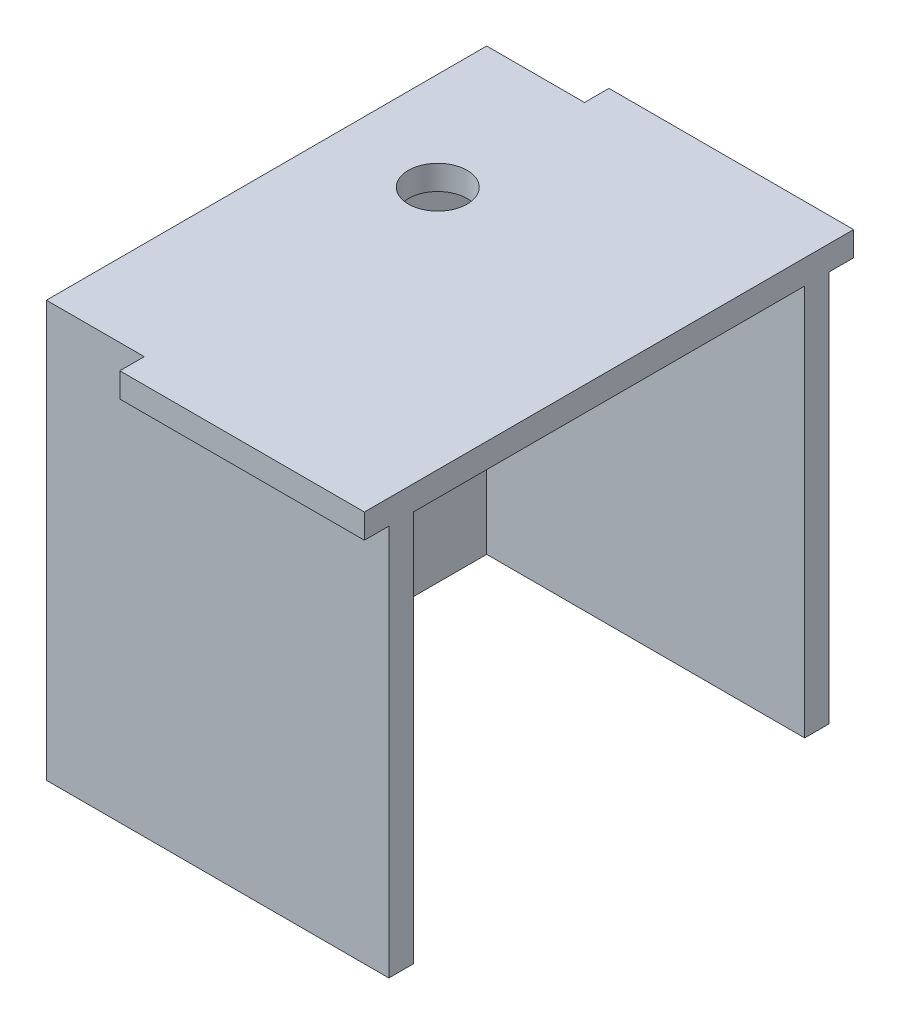
SolidWorks part; units mm, degrees
material "CA"
ref_plane "Front Plane" through (0, 0, 0) normal (0, 0, 1) x (1, 0, 0)
ref_plane "Top Plane" through (0, 0, 0) normal (0, 1, 0) x (1, 0, 0)
ref_plane "Right Plane" through (0, 0, 0) normal (1, 0, 0) x (0, 0, -1)
sketch "Sketch1" plane through (0, 0, 0) normal (0, 0, 1) x (1, 0, 0)
  line L1 (0, 0) -> (-65, 0)
  line L2 (0, 0) -> (0, 5)
  line L3 (0, 5) -> (-65, 5)
  line L6 (-65, 5) -> (-65, 30)
  line L7 (-65, 30) -> (-70, 30)
  line L8 (-70, 0) -> (-70, 30)
  line L10 (-65, 0) -> (-65, -80)
  line L11 (-65, -80) -> (-70, -80)
  line L12 (-70, 0) -> (-70, -80)
  dimension "D1" = 5
  dimension "D2" = 5
  dimension "D3" = 65
  dimension "D4" = 30
  dimension "D5" = 80
extrude "Boss-Extrude1" add sketch "Sketch1" along normal blind 100
sketch "Sketch2" plane through (0, 0, 100) normal (0, 0, 1) x (1, 0, 0)
  line L10 (-65, 0) -> (-70, 0)
  line L11 (-65, 0) -> (-65, -80)
  line L12 (-65, -80) -> (-70, -80)
  line L13 (-70, 0) -> (-70, -80)
extrude "Cut-Extrude2" cut sketch "Sketch2" against normal blind 5
sketch "Sketch3" plane through (0, 0, 0) normal (0, 0, -1) x (-1, 0, 0)
  line L1 (65, 0) -> (70, 0)
  line L2 (65, 0) -> (65, -80)
  line L3 (65, -80) -> (70, -80)
  line L4 (70, 0) -> (70, -80)
extrude "Cut-Extrude3" cut sketch "Sketch3" against normal blind 5
sketch "Sketch4" plane through (0, 0, 100) normal (0, 0, 1) x (1, 0, 0)
  line L0 (-70, 0) -> (0, 0) construction
  line L1 (-65, 5) -> (-50, 5)
  line L2 (-65, 5) -> (-65, 0)
  line L3 (-65, 0) -> (-50, 0)
  line L4 (-50, 5) -> (-50, 0)
  dimension "D1" = 15
extrude "Cut-Extrude4" cut sketch "Sketch4" against normal blind 5
sketch "Sketch5" plane through (0, 0, 0) normal (0, 0, -1) x (-1, 0, 0)
  line L0 (70, 0) -> (0, 0) construction
  line L1 (65, 5) -> (50, 5)
  line L2 (65, 5) -> (65, 0)
  line L3 (65, 0) -> (50, 0)
  line L4 (50, 5) -> (50, 0)
  dimension "D1" = 15
extrude "Cut-Extrude5" cut sketch "Sketch5" against normal blind 5
sketch "Sketch6" plane through (-65, 0, 0) normal (1, 0, 0) x (0, 0, -1)
  line L0 (-95, 0) -> (-5, 0) construction
  line L1 (-95, -80) -> (-95, 0) construction
  circle A0 centre (-50, -10) radius 1.5
  circle A1 centre (-50, -60.45) radius 1.5
  dimension "D2" = 3
  dimension "D4" = 3
  dimension "D1" = 10
  dimension "D3" = 50.45
  dimension "D5" = 45
  dimension "D6" = 45
extrude "Cut-Extrude6" cut sketch "Sketch6" against normal blind 10
sketch "Sketch7" plane through (-65, 0, 0) normal (1, 0, 0) x (0, 0, -1)
  line L0 (-95, -80) -> (-95, 0) construction
  line L1 (-95, -14.175) -> (-28.95, -14.175)
  line L2 (-95, -14.175) -> (-95, -56.275)
  line L3 (-95, -56.275) -> (-28.95, -56.275)
  line L4 (-28.95, -14.175) -> (-28.95, -56.275)
  line L5 (-95, 0) -> (-5, 0) construction
  dimension "D1" = 42.1
  dimension "D2" = 14.175
  dimension "D3" = 66.05
extrude "Cut-Extrude7" cut sketch "Sketch7" against normal blind 10
sketch "Sketch8" plane through (0, -14.175, 0) normal (0, -1, 0) x (1, 0, 0)
  line L0 (-70, 28.95) -> (-70, 95) construction
  line L1 (-65, 95) -> (-70, 95)
  line L2 (-65, 95) -> (-65, 75)
  line L3 (-65, 75) -> (-70, 75)
  line L4 (-70, 95) -> (-70, 75)
  dimension "D1" = 20
extrude "Boss-Extrude2" add sketch "Sketch8" along normal blind 42.1
sketch "Sketch10" plane through (0, 5, 0) normal (0, 1, 0) x (1, 0, 0)
  line L0 (-65, -95) -> (-65, -5) construction
  line L1 (0, -100) -> (-50, -100) construction
  circle A0 centre (-50, -35) radius 6
  dimension "D1" = 12
  dimension "D2" = 15
  dimension "D3" = 65
extrude "Cut-Extrude8" cut sketch "Sketch10" against normal blind 5
sketch "Sketch11" plane through (0, 0, 100) normal (0, 0, 1) x (1, 0, 0)
  line L0 (-70, 30) -> (-70, 0) construction
  line L1 (-65, 30) -> (-70, 30)
  line L2 (-65, 30) -> (-65, 5)
  line L3 (-65, 5) -> (-70, 5)
  line L4 (-70, 30) -> (-70, 5)
  dimension "D1" = 25
extrude "Cut-Extrude9" cut sketch "Sketch11" against normal blind 100
sketch "Sketch12" plane through (0, 0, 100) normal (0, 0, 1) x (1, 0, 0)
  line L1 (-65, 0) -> (-70, 0)
  line L2 (-65, 0) -> (-65, 5)
  line L3 (-65, 5) -> (-70, 5)
  line L4 (-70, 0) -> (-70, 5)
extrude "Cut-Extrude10" cut sketch "Sketch12" against normal blind 5
sketch "Sketch13" plane through (0, 0, 0) normal (0, 0, -1) x (-1, 0, 0)
  line L1 (65, 5) -> (70, 5)
  line L2 (65, 5) -> (65, 0)
  line L3 (65, 0) -> (70, 0)
  line L4 (70, 5) -> (70, 0)
extrude "Cut-Extrude11" cut sketch "Sketch13" against normal blind 5
sketch "Sketch14" plane through (-65, 0, 0) normal (1, 0, 0) x (0, 0, -1)
  line L0 (-95, 0) -> (-5, 0) construction
  line L1 (-95, -80) -> (-90, -80)
  line L2 (-95, -80) -> (-95, 0)
  line L3 (-95, 0) -> (-90, 0)
  line L4 (-90, -80) -> (-90, 0)
  line L6 (-5, -80) -> (-10, -80)
  line L7 (-5, -80) -> (-5, 0)
  line L8 (-5, 0) -> (-10, 0)
  line L9 (-10, -80) -> (-10, 0)
  dimension "D1" = 5
  dimension "D2" = 5
extrude "Boss-Extrude3" add sketch "Sketch14" along normal blind 65
